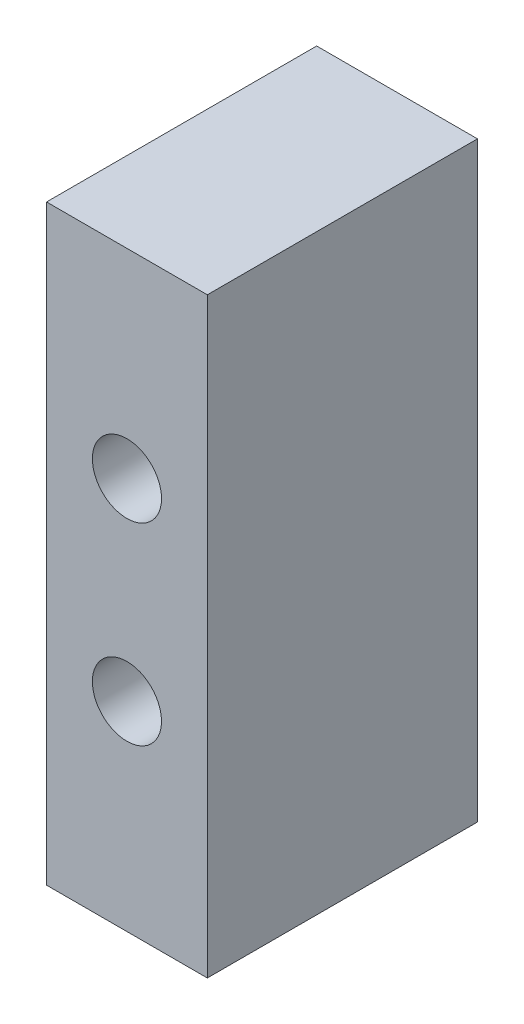
SolidWorks part; units mm, degrees
ref_plane "前视基准面" through (0, 0, 0) normal (0, 0, 1) x (1, 0, 0)
ref_plane "上视基准面" through (0, 0, 0) normal (0, 1, 0) x (1, 0, 0)
ref_plane "右视基准面" through (0, 0, 0) normal (1, 0, 0) x (0, 0, -1)
other "Configuration Table"
sketch "草图1" plane through (0, 0, 0) normal (0, 0, 1) x (1, 0, 0)
  line L0 (0, 0) -> (-21.1268, 0) construction
  line L1 (-5, 18.4) -> (5, 18.4)
  line L2 (-5, 18.4) -> (-5, -18.4)
  line L3 (-5, -18.4) -> (5, -18.4)
  line L4 (5, 18.4) -> (5, -18.4)
  line L5 (-5, 18.4) -> (5, -18.4) construction
  line L6 (-5, -18.4) -> (5, 18.4) construction
  circle A0 centre (0, 6) radius 2.15
  circle A1 centre (0, -6) radius 2.15
  point P0 (0, 0)
  point P12 (0, 0)
  dimension "D3" = 12
  dimension "D4" = 4.3
  dimension "D1" = 10
  dimension "D2" = 36.8
extrude "凸台-拉伸1" add sketch "草图1" along normal blind 16.8
